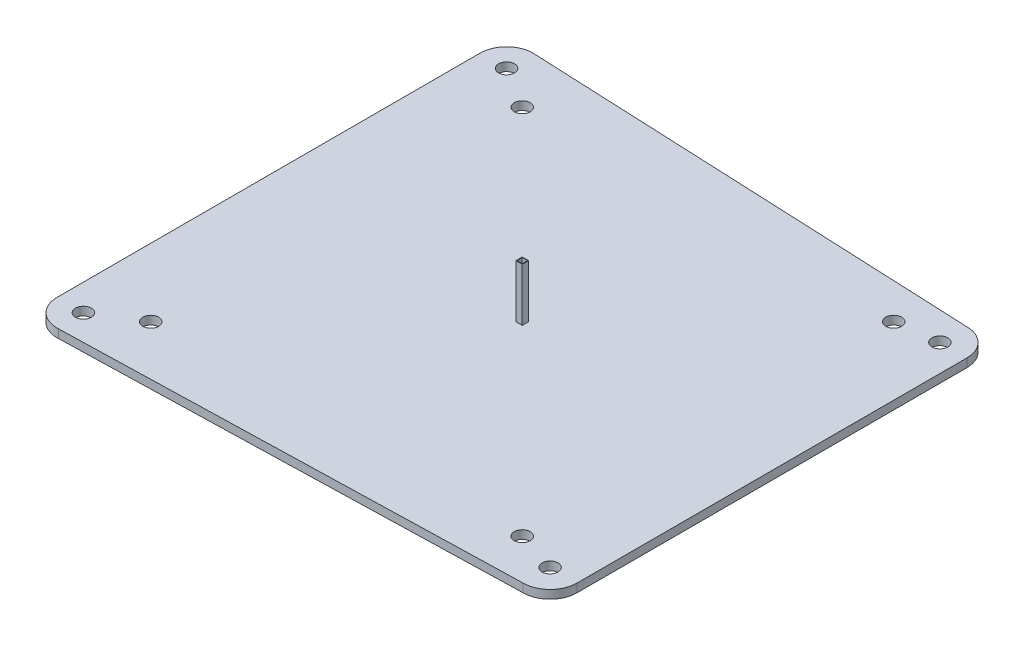
SolidWorks part; units mm, degrees
material "A-Glass Fiber"
ref_plane "Front Plane" through (0, 0, 0) normal (0, 0, 1) x (1, 0, 0)
ref_plane "Top Plane" through (0, 0, 0) normal (0, 1, 0) x (1, 0, 0)
ref_plane "Right Plane" through (0, 0, 0) normal (1, 0, 0) x (0, 0, -1)
sketch "Sketch1" plane through (0, 0, 0) normal (0, 1, 0) x (1, 0, 0)
  line L1 (-47.945, -45.085) -> (47.945, -45.085)
  line L2 (-47.945, -45.085) -> (-47.945, 45.085)
  line L3 (-47.945, 45.085) -> (47.945, 45.085)
  line L4 (47.945, -45.085) -> (47.945, 45.085)
  line L5 (-47.945, -45.085) -> (47.945, 45.085) construction
  line L6 (-47.945, 45.085) -> (47.945, -45.085) construction
  point P0 (0, 0)
  dimension "D1" = 95.89
  dimension "D2" = 90.17
extrude "Substrate" add sketch "Sketch1" along normal blind 1.6
sketch "Sketch2" plane through (0, 1.6, 0) normal (0, 1, 0) x (1, 0, 0)
  line L0 (-42.945, 39.9274) -> (-42.945, 50039.9274) construction
  line L2 (-47.945, -45.085) -> (47.945, -45.085) construction
  line L3 (-47.945, 45.085) -> (47.945, -45.085) construction
  line L4 (-47.945, 45.085) -> (-47.945, -45.085) construction
  line L5 (47.945, 45.085) -> (-47.945, 45.085) construction
  line L6 (47.945, -45.085) -> (47.945, 45.085) construction
  line L9 (47.945, -45.085) -> (-47.945, -45.085) construction
  circle A0 centre (42.845, 36.085) radius 1.5
  circle A1 centre (42.845, -37.585) radius 1.5
  circle A2 centre (-42.945, -39.985) radius 1.5
  circle A3 centre (-42.945, 39.985) radius 1.5
  dimension "D5" = 5.1
  dimension "D6" = 5
  dimension "D1" = 3
  dimension "D2" = 3
  dimension "D7" = 5.1
  dimension "D10" = 7.5
extrude "Cut-Extrude2" cut sketch "Sketch2" against normal blind 10
sketch "Sketch3" plane through (0, 1.6, 0) normal (0, 1, 0) x (1, 0, 0)
  line L0 (-47.945, 45.085) -> (47.945, -45.085) construction
  line L1 (-0.5, -0.5) -> (0.5, -0.5)
  line L2 (-0.5, -0.5) -> (-0.5, 0.5)
  line L3 (-0.5, 0.5) -> (0.5, 0.5)
  line L4 (0.5, -0.5) -> (0.5, 0.5)
  line L5 (-0.5, -0.5) -> (0.5, 0.5) construction
  line L6 (-0.5, 0.5) -> (0.5, -0.5) construction
  line L7 (-0.6, -0.6) -> (0.6, -0.6)
  line L8 (-0.6, -0.6) -> (-0.6, 0.6)
  line L9 (-0.6, 0.6) -> (0.6, 0.6)
  line L10 (0.6, -0.6) -> (0.6, 0.6)
  line L11 (-0.6, -0.6) -> (0.6, 0.6) construction
  line L12 (-0.6, 0.6) -> (0.6, -0.6) construction
  line L13 (47.945, -45.085) -> (47.945, 45.085) construction
  line L14 (47.945, 45.085) -> (-47.945, -45.085) construction
  point P0 (0, 0)
  point P6 (0, 0)
  dimension "D1" = 1
  dimension "D2" = 1
  dimension "D3" = 0.1
  dimension "D4" = 0.1
extrude "Boss-Extrude1" add sketch "Sketch3" along normal blind 10
sketch "Sketch4" plane through (0, 1.6, 0) normal (0, 1, 0) x (1, 0, 0)
  line L0 (-42.6771, -44.9778) -> (42.845, -42.685)
  line L1 (-47.945, -39.985) -> (-47.945, 39.985)
  line L2 (-42.5029, 44.9654) -> (42.845, 41.185)
  line L3 (47.945, 36.085) -> (47.945, -37.585)
  arc A0 (-47.945, -39.985) -> (-42.6771, -44.9778) centre (-42.945, -39.985) ccw
  arc A1 (-42.5029, 44.9654) -> (-47.945, 39.985) centre (-42.945, 39.985) ccw
  arc A2 (47.945, 36.085) -> (42.845, 41.185) centre (42.845, 36.085) ccw
  arc A3 (42.845, -42.685) -> (47.945, -37.585) centre (42.845, -37.585) ccw
extrude "Cut-Extrude3" cut sketch "Sketch4" against normal blind 10 flip side to cut
sketch "Sketch5" plane through (0, 1.6, 0) normal (0, 1, 0) x (1, 0, 0)
  line L1 (-38.1, -38.1) -> (38.1, -38.1) construction
  line L2 (-38.1, -38.1) -> (-38.1, 38.1) construction
  line L3 (-38.1, 38.1) -> (38.1, 38.1) construction
  line L4 (38.1, -38.1) -> (38.1, 38.1) construction
  line L5 (-38.1, -38.1) -> (38.1, 38.1) construction
  line L6 (-38.1, 38.1) -> (38.1, -38.1) construction
  circle A0 centre (-35.1, 35.1) radius 1.5
  circle A1 centre (35.1, 35.1) radius 1.5
  circle A2 centre (35.1, -35.1) radius 1.5
  circle A3 centre (-35.1, -35.1) radius 1.5
  point P0 (0, 0)
  dimension "D6" = 3
  dimension "D8" = 3
  dimension "D9" = 3
  dimension "D10" = 3
  dimension "D1" = 76.2
  dimension "D2" = 76.2
  dimension "D3" = 3
  dimension "D4" = 3
  dimension "D5" = 3
  dimension "D7" = 3
extrude "Cut-Extrude4" cut sketch "Sketch5" against normal blind 10
